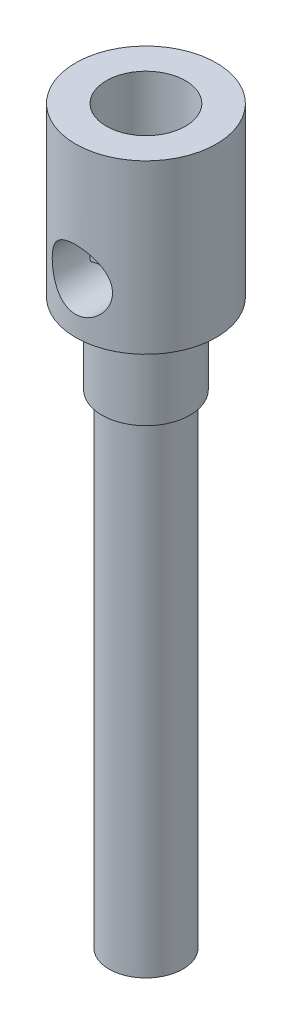
SolidWorks part; units mm, degrees
material "1023 Carbon Steel Sheet (SS)"
ref_plane "Front Plane" through (0, 0, 0) normal (0, 0, 1) x (1, 0, 0)
ref_plane "Top Plane" through (0, 0, 0) normal (0, 1, 0) x (1, 0, 0)
ref_plane "Right Plane" through (0, 0, 0) normal (1, 0, 0) x (0, 0, -1)
sketch "Sketch1" plane through (0, 0, 0) normal (0, 1, 0) x (1, 0, 0)
  circle A0 centre (0, 0) radius 2.58
  circle A1 centre (0, 0) radius 5.5
  circle A2 centre (0, 0) radius 4.58 construction
  dimension "D1" = 2
  dimension "D2" = 11
  dimension "D3" = 5.16
  dimension "D4" = 9.16
extrude "Boss-Extrude1" add sketch "Sketch1" along normal blind 72.14
sketch "Sketch2" plane through (0, 0, 0) normal (0, -1, 0) x (1, 0, 0)
  circle A0 centre (0, 0) radius 5.5
  circle A1 centre (0, 0) radius 5.5 construction
  circle A2 centre (0, 0) radius 5.5
  dimension "D1" = 11
sketch "Sketch4" plane through (0, 72.14, 0) normal (0, 1, 0) x (1, 0, 0)
  circle A0 centre (0, 0) radius 3.4
  circle A2 centre (0, 0) radius 5.5 construction
  dimension "D1" = 6.8
  dimension "D2" = 2.1
sketch "Sketch5" plane through (0, 72.14, 0) normal (0, 1, 0) x (1, 0, 0)
  circle A0 centre (0, 0) radius 6.5785
  dimension "D1" = 13.157
extrude "Boss-Extrude2" add sketch "Sketch5" along normal blind 12
sketch "Sketch6" plane through (0, 84.14, 0) normal (0, 1, 0) x (1, 0, 0)
  circle A0 centre (0, 0) radius 10.5
  dimension "D1" = 21
extrude "Boss-Extrude3" add sketch "Sketch6" along normal blind 25
hole_wizard "G1/4 Tapped Hole2" positions "Sketch10" profile "Sketch11" tap size "G1/4" standard "ISO"
sketch "Sketch10" plane through (0, 109.14, 0) normal (0, 1, 0) x (1, 0, 0)
  point P0 (0, 0)
sketch "Sketch11" plane through (0, 109.14, 0) normal (1, 0, 0) x (0, 0, 1)
  line L0 (0, 0) -> (0, 23.5451)
  line L1 (0, 23.5451) -> (5.9, 20)
  line L2 (5.9, 20) -> (5.9, 0)
  line L5 (5.9, 0) -> (0, 0)
  line L10 (0, 23.5451) -> (-5.9, 20) construction
  line L11 (0, -6.35) -> (0, 107.95) construction
  dimension "Tap Drill Dia." = 11.8
  dimension "Tap Drill Depth" = 20
  dimension "Drill Angle" = 118
cosmetic thread "Hole Thread7" parameters "D1"=15, "D2"=13.157
ref_plane "Plane1" through (0, 90.14, 0) normal (0, -1, 0) x (-1, 0, 0)
sketch "Sketch15" plane through (0, 90.14, 0) normal (0, -1, 0) x (-1, 0, 0)
  circle A0 centre (0, 0) radius 2.5
  dimension "D1" = 5
extrude "Boss-Extrude4" add sketch "Sketch15" along normal up to surface (18 mm away) contours A0
hole_wizard "M8 Tapped Hole1" positions "Sketch16" profile "Sketch17" tap size "M8" standard "ISO"
sketch "Sketch16" plane through (0, 90.14, 0) normal (0, 1, 0) x (1, 0, 0)
  point P0 (0, 0)
sketch "Sketch17" plane through (0, 90.14, 0) normal (1, 0, 0) x (0, 0, 1)
  line L0 (0, 0) -> (0, 81.1829)
  line L1 (0, 81.1829) -> (3.4, 79.14)
  line L2 (3.4, 79.14) -> (3.4, 0)
  line L5 (3.4, 0) -> (0, 0)
  line L10 (0, 81.1829) -> (-3.4, 79.14) construction
  line L11 (0, -6.35) -> (0, 107.95) construction
  dimension "Tap Drill Dia." = 6.8
  dimension "Tap Drill Depth" = 79.14
  dimension "Drill Angle" = 118
cosmetic thread "Hole Thread2" parameters "D1"=10, "D2"=8
sketch "Sketch18" plane through (0, 0, 0) normal (0, 0, 1) x (1, 0, 0)
  line L0 (0, 87.14) -> (0, 91.64) construction
  line L2 (5.9, 87.14) -> (-5.9, 87.14) construction
  circle A0 centre (0, 91.64) radius 4.5
  point P7 (0, 87.14)
  dimension "D2" = 9
extrude "Cut-Extrude1" cut sketch "Sketch18" along normal blind 20 contours A0
equation "\"D1@Sketch6\"=21"
